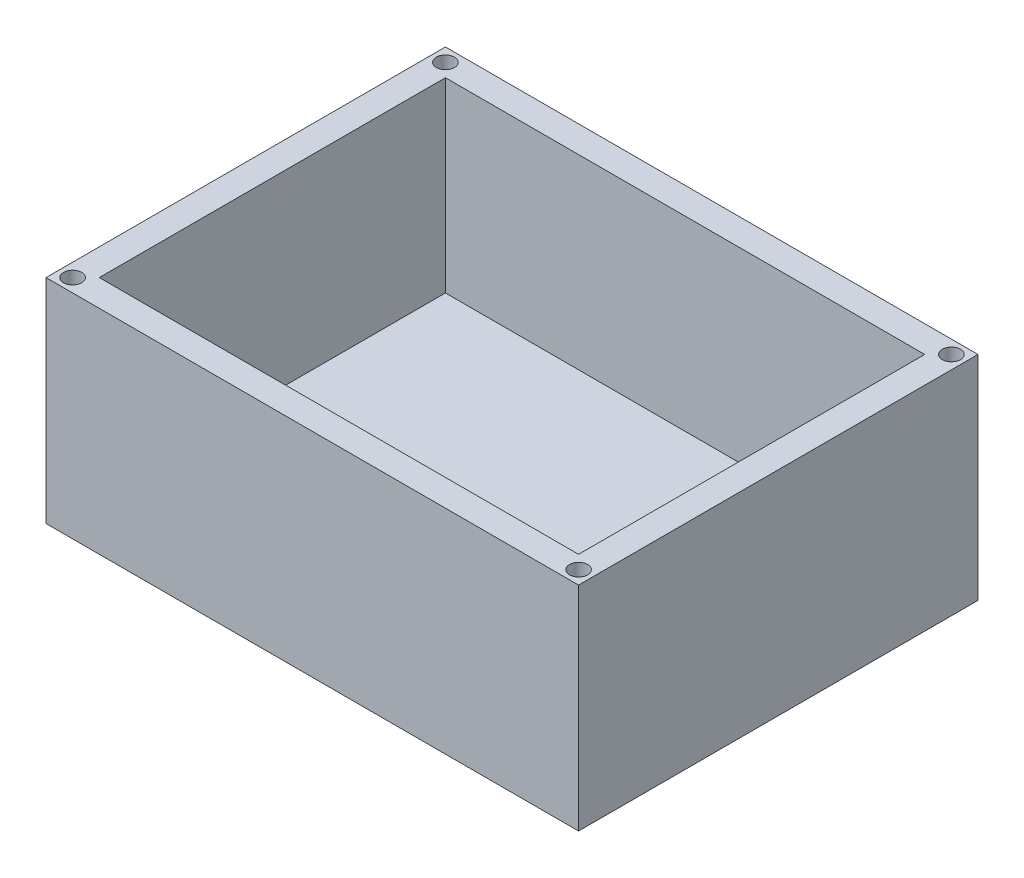
SolidWorks part; units mm, degrees
ref_plane "Alzado" through (0, 0, 0) normal (0, 0, 1) x (1, 0, 0)
ref_plane "Planta" through (0, 0, 0) normal (0, 1, 0) x (1, 0, 0)
ref_plane "Vista lateral" through (0, 0, 0) normal (1, 0, 0) x (0, 0, -1)
sketch "Croquis1" plane through (0, 0, 0) normal (0, 1, 0) x (1, 0, 0)
  line L0 (-24.9817, 14.2814) -> (75.0183, 14.2814)
  line L1 (75.0183, 14.2814) -> (75.0183, -60.7186)
  line L2 (75.0183, -60.7186) -> (-24.9817, -60.7186)
  line L3 (-24.9817, 14.2814) -> (-24.9817, -60.7186)
  dimension "D1" = 100
  dimension "D2" = 75
extrude "Saliente-Extruir1" add sketch "Croquis1" along normal blind 40
sketch "Croquis2" plane through (0, 0, 0) normal (0, 1, 0) x (1, 0, 0)
  line L0 (75.0183, -60.7186) -> (75.0183, 14.2814) construction
  line L1 (-19.9817, 9.2814) -> (70.0183, 9.2814)
  line L2 (-19.9817, 9.2814) -> (-19.9817, -55.7186)
  line L3 (-19.9817, -55.7186) -> (70.0183, -55.7186)
  line L4 (70.0183, 9.2814) -> (70.0183, -55.7186)
  line L5 (-24.9817, -60.7186) -> (75.0183, -60.7186) construction
  dimension "D1" = 65
  dimension "D2" = 90
  dimension "D3" = 5
  dimension "D4" = 5
extrude "Cortar-Extruir1" cut sketch "Croquis2" along normal through all
sketch "Croquis3" plane through (0, 0, 0) normal (0, 1, 0) x (1, 0, 0)
  line L1 (-19.9817, 9.2814) -> (70.0183, 9.2814)
  line L2 (-19.9817, 9.2814) -> (-19.9817, -55.7186)
  line L3 (-19.9817, -55.7186) -> (70.0183, -55.7186)
  line L4 (70.0183, 9.2814) -> (70.0183, -55.7186)
extrude "Saliente-Extruir2" add sketch "Croquis3" along normal blind 5
ref_plane "Plano1" through (0, 40, 0) normal (0, -1, 0) x (-1, 0, 0)
sketch "Croquis5" plane through (0, 40, 0) normal (0, -1, 0) x (-1, 0, 0)
  line L0 (-75.0183, 14.2814) -> (24.9817, 14.2814) construction
  line L1 (24.9817, 14.2814) -> (24.9817, -60.7186) construction
  line L2 (-75.0183, -60.7186) -> (-75.0183, 14.2814) construction
  line L3 (24.9817, -60.7186) -> (-75.0183, -60.7186) construction
  point P0 (22.4817, 11.7814)
  point P1 (-72.5183, 11.7814)
  point P2 (-72.5183, -58.2186)
  point P3 (22.4817, -58.2186)
  dimension "D1" = 2.5
  dimension "D2" = 2.5
  dimension "D3" = 2.5
  dimension "D4" = 2.5
  dimension "D5" = 2.5
  dimension "D6" = 2.5
  dimension "D7" = 2.5
  dimension "D8" = 2.5
hole_wizard "Taladro de margen para M31" positions "Croquis3D2" profile "Croquis7" hole size "M3" standard "DIN"
sketch3d "Croquis3D2"
  line L0 (-24.9817, 40, 60.7186) -> (75.0183, 40, 60.7186) construction
  line L1 (75.0183, 40, 60.7186) -> (75.0183, 40, -14.2814) construction
  point P0 (-22.4817, 40, -11.7814)
  point P2 (72.5183, 40, -11.7814)
  point P4 (72.5183, 40, 58.2186)
  point P7 (72.5183, 40, 58.2186)
  point P9 (-22.4817, 40, 58.2186)
  dimension "D1" = 2.5
  dimension "D2" = 2.5
  dimension "D3" = 2.5
  dimension "D4" = 2.5
sketch "Croquis7" plane through (-22.4817, 40, -11.7814) normal (1, 0, 0) x (0, 0, 1)
  line L0 (0, 0) -> (0, 21.0215)
  line L1 (0, 21.0215) -> (1.7, 20)
  line L2 (1.7, 20) -> (1.7, 0)
  line L5 (1.7, 0) -> (0, 0)
  line L10 (0, 21.0215) -> (-1.7, 20) construction
  line L11 (0, -6.35) -> (0, 107.95) construction
  dimension "Diámetro de taladro" = 3.4
  dimension "Profundidad de taladro" = 20
  dimension "Ángulo de perforador" = 118
